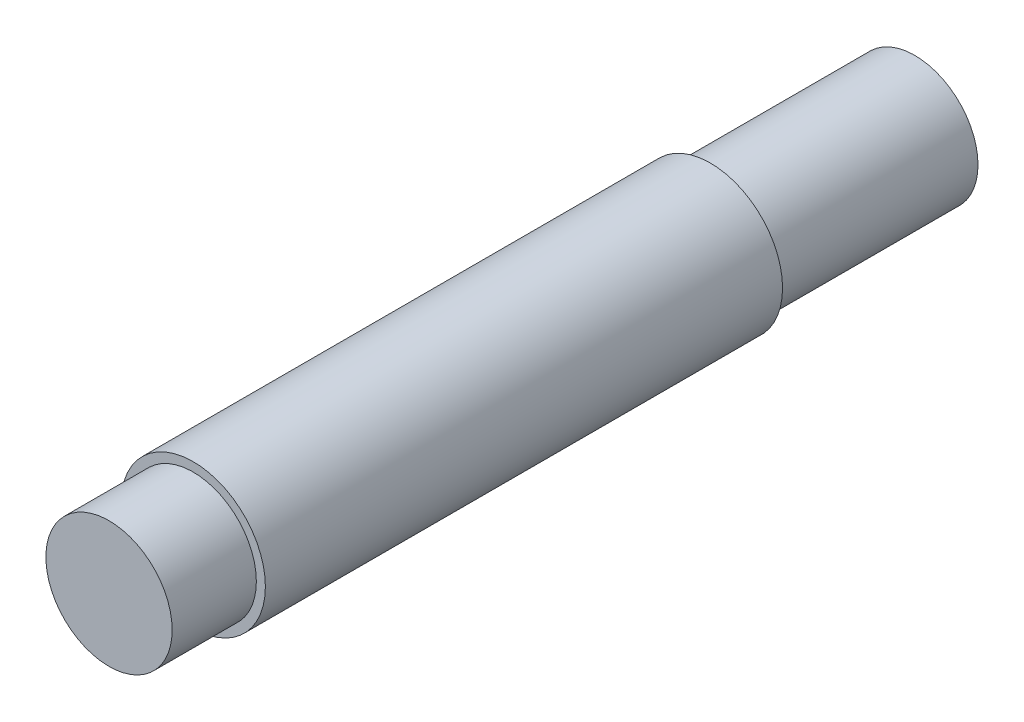
SolidWorks part; units mm, degrees
material "AISI 304"
ref_plane "Front Plane" through (0, 0, 0) normal (0, 0, 1) x (1, 0, 0)
ref_plane "Top Plane" through (0, 0, 0) normal (0, 1, 0) x (1, 0, 0)
ref_plane "Right Plane" through (0, 0, 0) normal (1, 0, 0) x (0, 0, -1)
sketch "Sketch1" plane through (0, 0, 0) normal (1, 0, 0) x (0, 0, -1)
  line L0 (-7, 0) -> (60, 0)
  line L1 (60, 0) -> (60, 5.25)
  line L2 (60, 5.25) -> (43, 5.25)
  line L3 (43, 5.25) -> (43, 6)
  line L4 (43, 6) -> (0, 6)
  line L5 (0, 6) -> (0, 5.25)
  line L6 (0, 5.25) -> (-7, 5.25)
  line L7 (-7, 5.25) -> (-7, 0)
  dimension "D1" = 7
  dimension "D2" = 50
  dimension "D3" = 67
  dimension "D4" = 5.25
  dimension "D5" = 6
revolve "Revolve1" add sketch "Sketch1" angle 360 about L0
